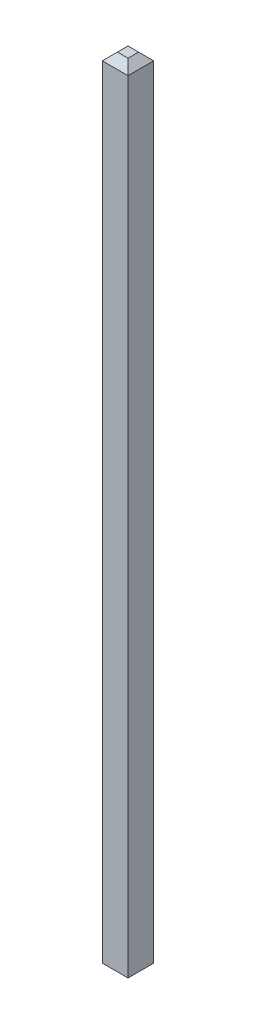
SolidWorks part; units mm, degrees
ref_plane "Front Plane" through (0, 0, 0) normal (0, 0, 1) x (1, 0, 0)
ref_plane "Top Plane" through (0, 0, 0) normal (0, 1, 0) x (1, 0, 0)
ref_plane "Right Plane" through (0, 0, 0) normal (1, 0, 0) x (0, 0, -1)
sketch "Sketch2" plane through (0, 0, 0) normal (0, 1, 0) x (1, 0, 0)
  line L1 (-0.34, -0.34) -> (0.34, -0.34)
  line L2 (-0.34, -0.34) -> (-0.34, 0.34)
  line L3 (-0.34, 0.34) -> (0.34, 0.34)
  line L4 (0.34, -0.34) -> (0.34, 0.34)
  line L5 (-0.34, -0.34) -> (0.34, 0.34) construction
  line L6 (-0.34, 0.34) -> (0.34, -0.34) construction
  point P1 (0, 0)
  dimension "D1" = 0.68
  dimension "D2" = 0.68
extrude "Boss-Extrude1" add sketch "Sketch2" along normal blind 21.08
chamfer "Chamfer1" distance 0.2 angle 45 8 edges at (0, 0, -0.34) (-0.34, 0, 0) (0, 0, 0.34) (0.34, 0, 0) (0, 21.08, 0.34) (-0.34, 21.08, 0) (0, 21.08, -0.34) (0.34, 21.08, 0)
